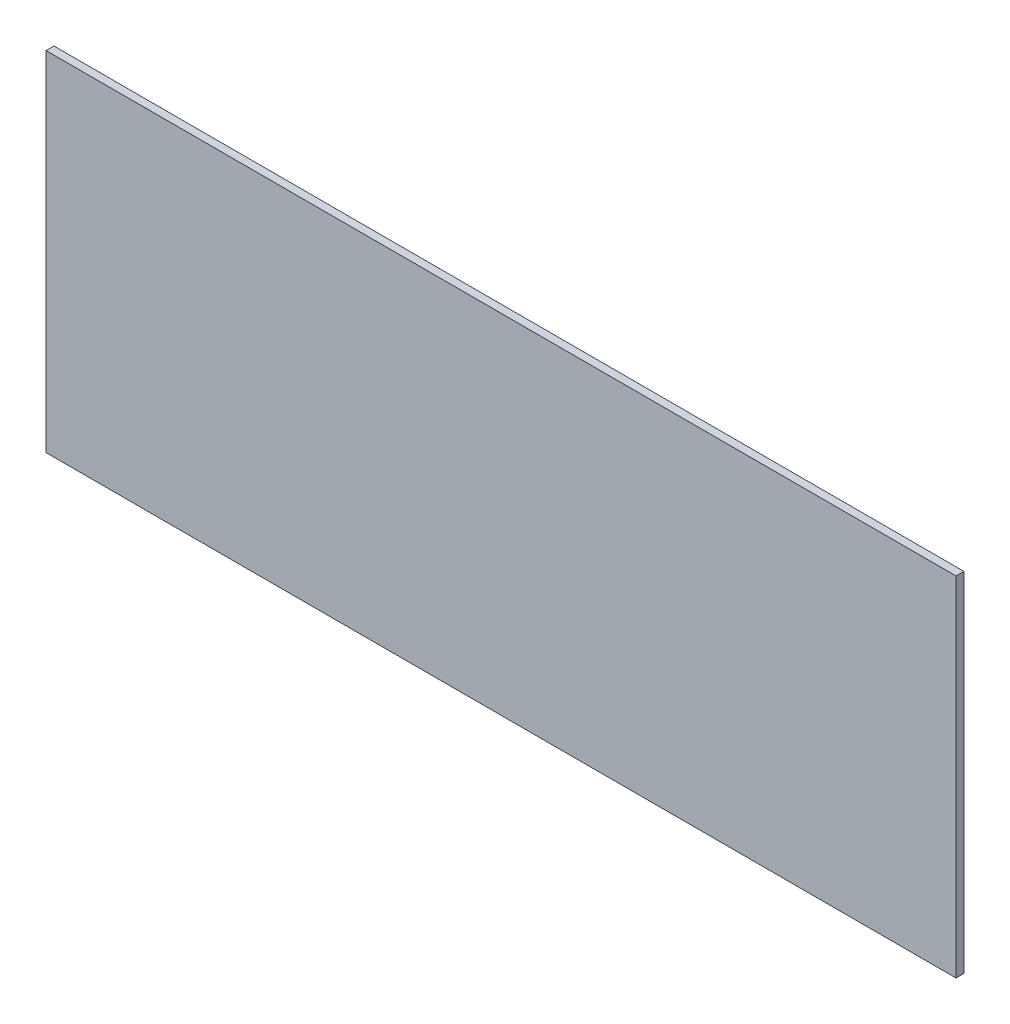
SolidWorks part; units mm, degrees
ref_plane "Front Plane" through (0, 0, 0) normal (0, 0, 1) x (1, 0, 0)
ref_plane "Top Plane" through (0, 0, 0) normal (0, 1, 0) x (1, 0, 0)
ref_plane "Right Plane" through (0, 0, 0) normal (1, 0, 0) x (0, 0, -1)
sketch "Sketch1" plane through (0, 0, 0) normal (0, 0, 1) x (1, 0, 0)
  line L1 (-575, 220) -> (575, 220)
  line L2 (-575, 220) -> (-575, -220)
  line L3 (-575, -220) -> (575, -220)
  line L4 (575, 220) -> (575, -220)
  line L5 (-575, 220) -> (575, -220) construction
  line L6 (-575, -220) -> (575, 220) construction
  point P0 (0, 0)
  dimension "D1" = 440
  dimension "D2" = 1150
extrude "Boss-Extrude1" add sketch "Sketch1" along normal blind 10
